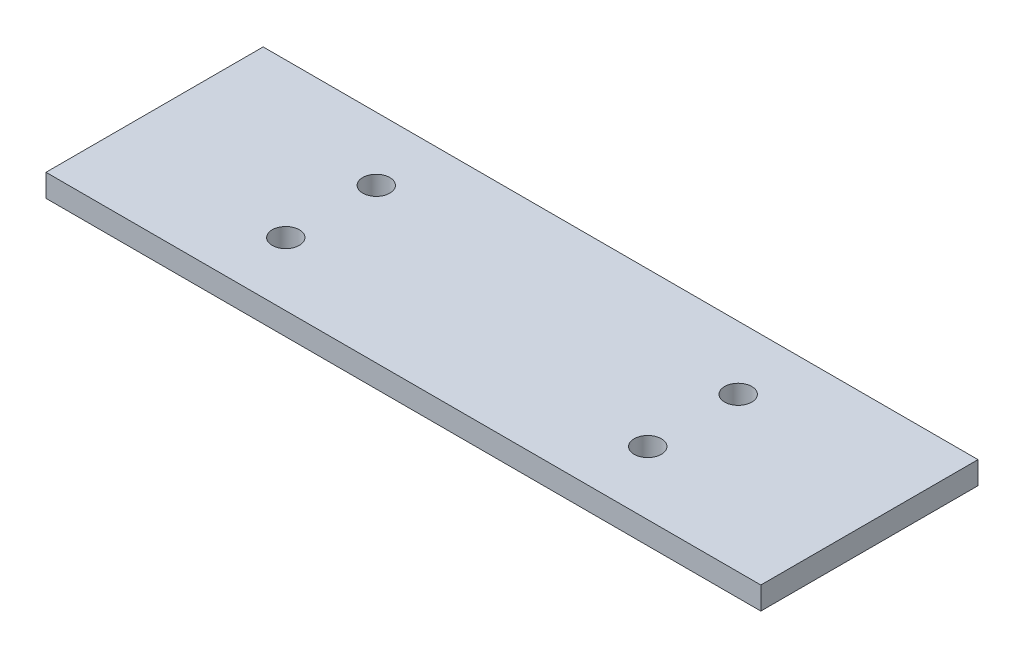
SolidWorks part; units mm, degrees
ref_plane "Ebene vorne" through (0, 0, 0) normal (0, 0, 1) x (1, 0, 0)
ref_plane "Ebene oben" through (0, 0, 0) normal (0, 1, 0) x (1, 0, 0)
ref_plane "Ebene rechts" through (0, 0, 0) normal (1, 0, 0) x (0, 0, -1)
sketch "Skizze1" plane through (0, 0, 0) normal (0, 1, 0) x (1, 0, 0)
  line L1 (-80, -25) -> (80, -25)
  line L2 (-80, -25) -> (-80, 25)
  line L3 (-80, 25) -> (80, 25)
  line L4 (80, -25) -> (80, 25)
  line L5 (-80, -25) -> (80, 25) construction
  line L6 (-80, 25) -> (80, -25) construction
  circle A0 centre (-40, 10) radius 3
  circle A1 centre (-40, -10) radius 3
  circle A2 centre (40, 10) radius 3
  circle A3 centre (40, -10) radius 3
  point P0 (0, 0)
  dimension "D3" = 6
  dimension "D4" = 6
  dimension "D5" = 6
  dimension "D6" = 6
  dimension "D1" = 160
  dimension "D2" = 50
  dimension "D7" = 80
  dimension "D8" = 40
  dimension "D9" = 40
  dimension "D10" = 80
  dimension "D11" = 40
  dimension "D12" = 15
  dimension "D13" = 15
  dimension "D14" = 20
  dimension "D15" = 15
extrude "Aufsatz-Linear austragen1" add sketch "Skizze1" along normal blind 5
sketch "Skizze2" plane through (0, 5, 0) normal (0, 1, 0) x (1, 0, 0)
  line L0 (80, 25) -> (-80, 25) construction
  line L1 (-79, 24) -> (79, 24)
  line L2 (-79, 24) -> (-79, -24)
  line L3 (-79, -24) -> (79, -24)
  line L4 (79, 24) -> (79, -24)
  line L5 (-80, 25) -> (-80, -25) construction
  line L6 (-80, -25) -> (80, -25) construction
  line L7 (80, -25) -> (80, 25) construction
  line L9 (-80, 25) -> (80, 25)
  line L10 (-80, 25) -> (-80, -25)
  line L11 (-80, -25) -> (80, -25)
  line L12 (80, 25) -> (80, -25)
  dimension "D1" = 1
  dimension "D2" = 1
  dimension "D3" = 1
  dimension "D4" = 1
extrude "Schnitt-Linear austragen1" cut sketch "Skizze2" against normal blind 10
